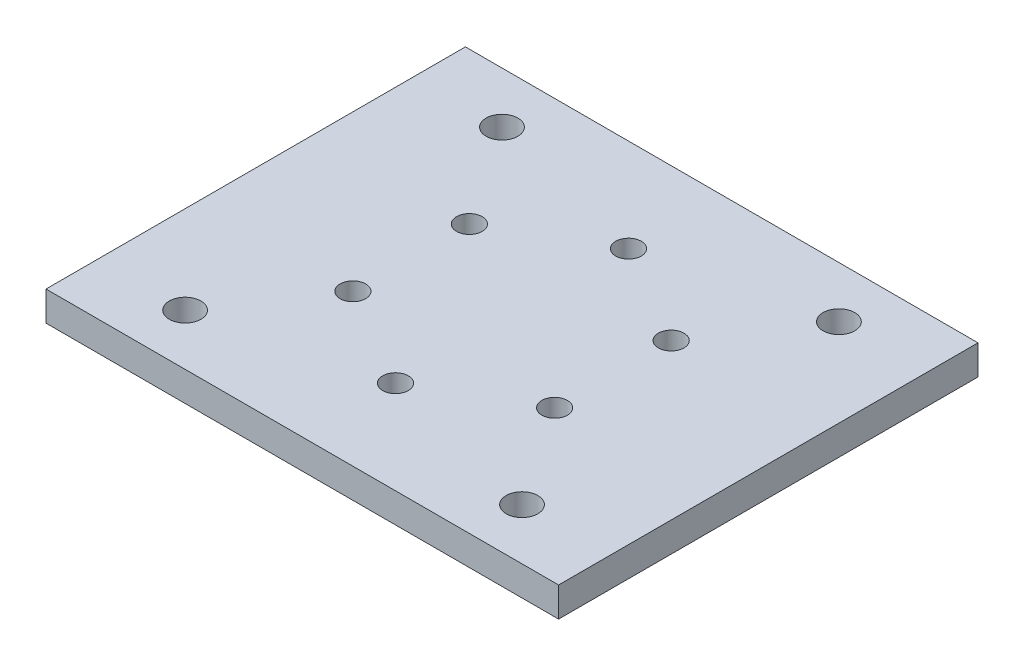
SolidWorks part; units mm, degrees
ref_plane "Front Plane" through (0, 0, 0) normal (0, 0, 1) x (1, 0, 0)
ref_plane "Top Plane" through (0, 0, 0) normal (0, 1, 0) x (1, 0, 0)
ref_plane "Right Plane" through (0, 0, 0) normal (1, 0, 0) x (0, 0, -1)
sketch "Sketch2" plane through (0, 0, 0) normal (0, 1, 0) x (1, 0, 0)
  line L0 (0, 0) -> (0, 90)
  line L1 (0, 90) -> (110, 90)
  line L2 (110, 90) -> (110, 0)
  line L3 (110, 0) -> (0, 0)
  dimension "D1" = 110
  dimension "D2" = 90
extrude "Boss-Extrude1" add sketch "Sketch2" along normal blind 6.35
sketch "Sketch3" plane through (0, 6.35, 0) normal (0, 1, 0) x (1, 0, 0)
  line L1 (110, 90) -> (0, 90) construction
  line L2 (0, 0) -> (110, 0) construction
  line L4 (55, 90) -> (55, 0) construction
  line L5 (0, 45) -> (55, 45) construction
  line L6 (55, 45) -> (110, 45) construction
  line L7 (0, 90) -> (0, 0) construction
  circle A0 centre (18.85, 79) radius 3.4
  circle A1 centre (18.85, 11) radius 3.4
  circle A2 centre (91.15, 11) radius 3.4
  circle A3 centre (91.15, 79) radius 3.4
  dimension "D4" = 6.8
  dimension "D3" = 11
  dimension "D2" = 18.85
extrude "Mounting Holes" cut sketch "Sketch3" against normal through all
sketch "Sketch4" plane through (0, 6.35, 0) normal (0, 1, 0) x (1, 0, 0)
  line L0 (18.85, 79) -> (91.15, 11) construction
  circle A0 centre (55, 45) radius 25 construction
  circle A1 centre (55, 70) radius 2.75
  circle A2 centre (76.6506, 57.5) radius 2.75
  circle A3 centre (76.6506, 32.5) radius 2.75
  circle A4 centre (55, 20) radius 2.75
  circle A5 centre (33.3494, 32.5) radius 2.75
  circle A6 centre (33.3494, 57.5) radius 2.75
  point P20 (55, 45)
  dimension "D1" = 50
  dimension "D2" = 5.5
  dimension "D3" = 6
extrude "Cut-Extrude1" cut sketch "Sketch4" against normal through all
sketch "Sketch5" plane through (0, 6.35, 0) normal (0, 1, 0) x (1, 0, 0)
  circle A0 centre (55, 45) radius 25 construction
  circle A1 centre (55, 20) radius 2.75 construction
  circle A2 centre (55, 20) radius 2.75 construction
  circle A3 centre (33.3494, 32.5) radius 2.75 construction
  circle A4 centre (33.3494, 32.5) radius 2.75 construction
  circle A5 centre (33.3494, 57.5) radius 2.75 construction
  circle A6 centre (33.3494, 57.5) radius 2.75 construction
equation "\"L1L\"=500"
equation "\"L1Thick\"=6.35"
equation "\"Harm-Drive-Outer\"=74.5"
equation "\"L1-Spacing\"=100"
equation "\"L-Bracket-HoleToWall\"=12.5"
equation "\"D3@Sketch3\"=\"L-Bracket-HoleToSide\""
equation "\"L-Bracket-HoleToSide\"=11"
equation "\"Bracket-Hole-D\"=6.8"
equation "\"D4@Sketch3\"=\"Bracket-Hole-D\""
equation "\"L1-Spacing\"=115.65"
equation "\"D2@Sketch3\"=\"L-Bracket-HoleToWall\"+\"L1Thick\""
